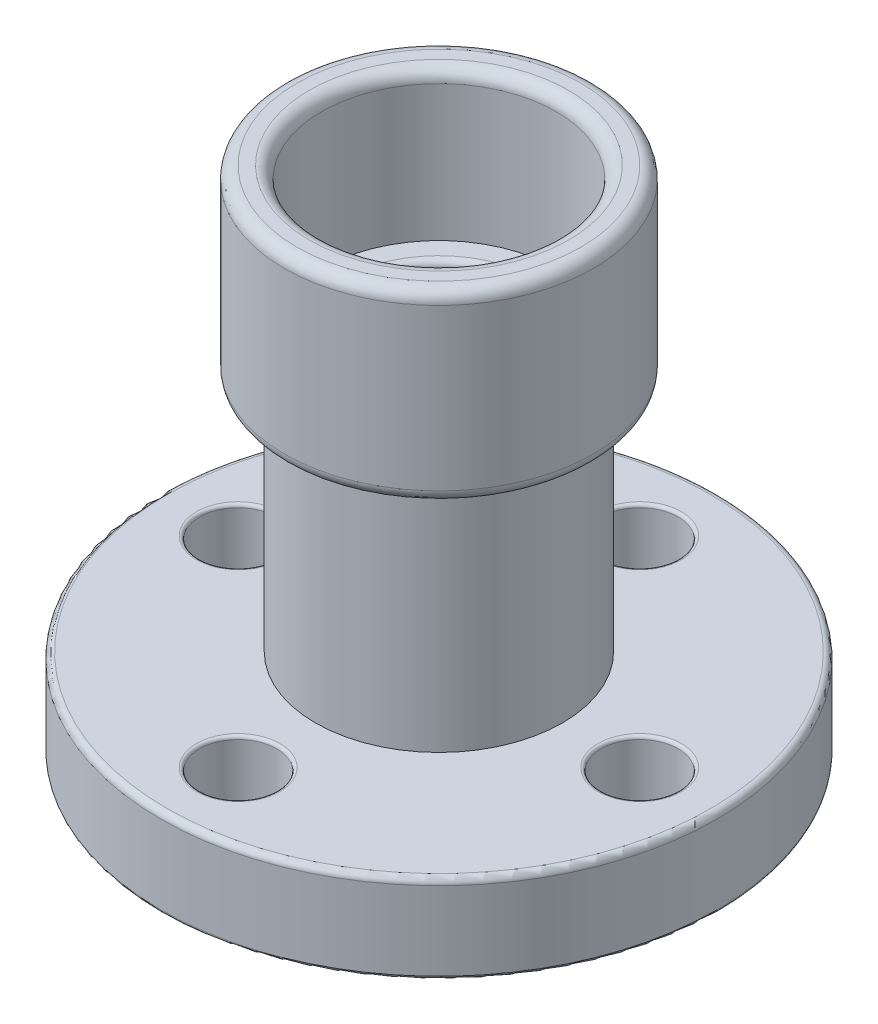
SolidWorks part; units mm, degrees
ref_plane "Front Plane" through (0, 0, 0) normal (0, 0, 1) x (1, 0, 0)
ref_plane "Top Plane" through (0, 0, 0) normal (0, 1, 0) x (1, 0, 0)
ref_plane "Right Plane" through (0, 0, 0) normal (1, 0, 0) x (0, 0, -1)
sketch "Sketch1" plane through (0, 0, 0) normal (0, 1, 0) x (1, 0, 0)
  circle A0 centre (0, 0) radius 45
  circle A1 centre (0, 0) radius 15
  circle A2 centre (0, 0) radius 20
  dimension "D1" = 90
  dimension "D2" = 30
  dimension "D3" = 40
extrude "Boss-Extrude2" add sketch "Sketch1" against normal blind 14.2 contours A0 A2 | A2 A1
sketch "Sketch2" plane through (0, 0, 0) normal (0, 1, 0) x (1, 0, 0)
  circle A0 centre (0, 0) radius 15 construction
  circle A1 centre (0, 0) radius 15
  circle A2 centre (0, 0) radius 15
  circle A3 centre (0, 0) radius 20
  circle M2 centre (0, 0) radius 15
  dimension "D2" = 40
  dimension "D1" = 0
extrude "Boss-Extrude3" add sketch "Sketch2" along normal blind 44.2 contours A3 M2
sketch "Sketch3" plane through (0, 44.2, 0) normal (0, 1, 0) x (1, 0, 0)
  circle A1 centre (0, 0) radius 15 construction
  circle A3 centre (0, 0) radius 15
  circle A5 centre (0, 0) radius 19
  circle A6 centre (0, 0) radius 25
  circle M2 centre (0, 0) radius 20
  dimension "D2" = 38
  dimension "D3" = 50
extrude "Boss-Extrude4" add sketch "Sketch3" along normal blind 24 contours A5 M2 | A6 M2
sketch "Sketch4" plane through (0, 44.2, 0) normal (0, -1, 0) x (1, 0, 0)
  circle A0 centre (0, 0) radius 15 construction
  circle A1 centre (0, 0) radius 25
  circle A2 centre (0, 0) radius 25
  circle A3 centre (0, 0) radius 15
  dimension "D1" = 0
extrude "Boss-Extrude5" add sketch "Sketch4" along normal blind 6
sketch "Sketch5" plane through (0, 0, 0) normal (0, 1, 0) x (1, 0, 0)
  line L0 (-65.2658, 0) -> (88.2343, 0) construction
  line L1 (0, 60.6369) -> (0, -54.1304) construction
  circle A0 centre (0, 32.5) radius 6.25
  circle A1 centre (32.5, 0) radius 6.25
  circle A2 centre (0, -32.5) radius 6.25
  circle A3 centre (-32.5, 0) radius 6.25
  point P16 (0, 0)
  dimension "D1" = 12.5
  dimension "D2" = 32.5
  dimension "D3" = 4
extrude "Cut-Extrude1" cut sketch "Sketch5" against normal blind 24
fillet "Fillet1" radius 1 1 edges at (0, 0, 45)
fillet "Fillet2" radius 2 3 edges at (0, 38.2, -25) (0, 68.2, 25) (0, 68.2, 19)
fillet "Fillet3" radius 1 1 edges at (0, 44.2, 15)
fillet "Fillet4" radius 0.5 4 edges at (0, 0, -26.25) (32.5, 0, 6.25) (-32.5, 0, 6.25) (0, 0, 38.75)
fillet "Fillet5" radius 0.5 1 edges at (0, -14.2, 45)
fillet "Fillet6" radius 1 1 edges at (0, -14.2, 15)
